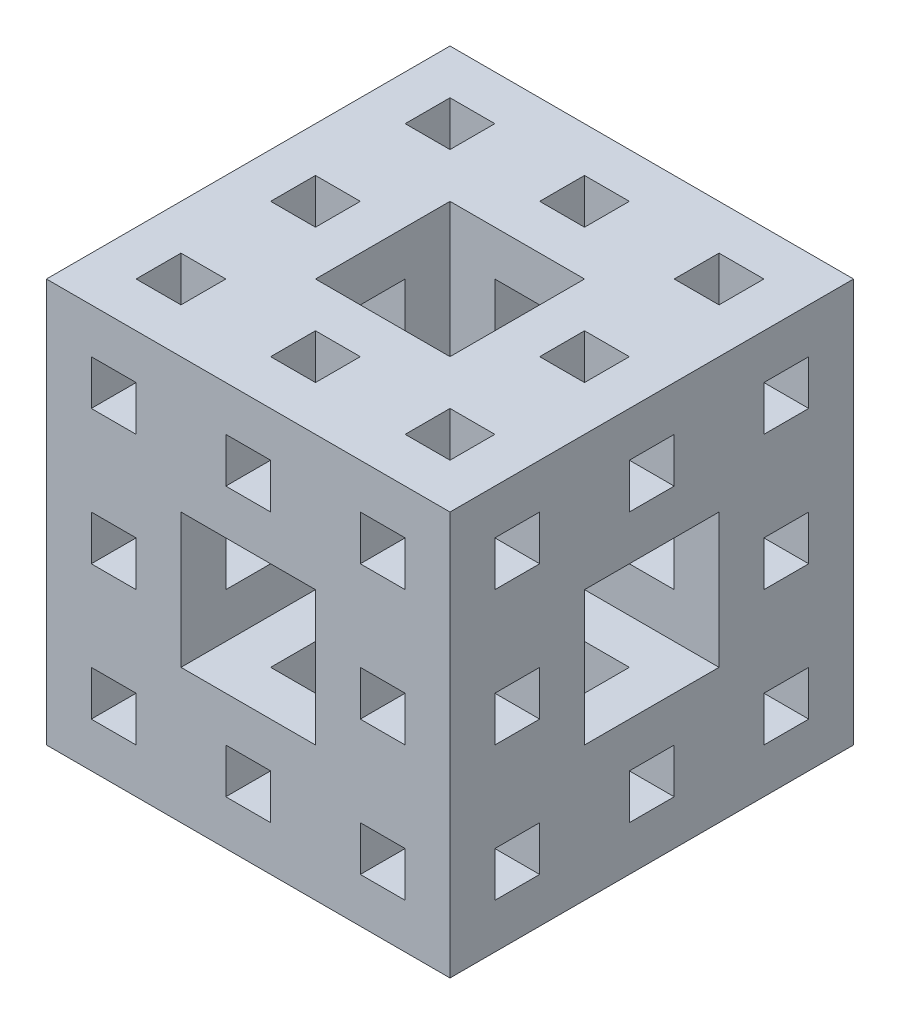
SolidWorks part; units mm, degrees
ref_plane "前视基准面" through (0, 0, 0) normal (0, 0, 1) x (1, 0, 0)
ref_plane "上视基准面" through (0, 0, 0) normal (0, 1, 0) x (1, 0, 0)
ref_plane "右视基准面" through (0, 0, 0) normal (1, 0, 0) x (0, 0, -1)
sketch "草图1" plane through (0, 0, 0) normal (0, 0, 1) x (1, 0, 0)
  line L0 (0, 0) -> (81, 0)
  line L1 (81, 0) -> (81, 81)
  line L2 (81, 81) -> (0, 81)
  line L3 (0, 81) -> (0, 0)
extrude "凸台-拉伸1" add sketch "草图1" along normal blind 81
sketch "草图2" plane through (0, 0, 0) normal (1, 0, 0) x (0, 0, -1)
  line L0 (-27, 27) -> (-54, 27)
  line L1 (-54, 27) -> (-54, 54)
  line L2 (-54, 54) -> (-27, 54)
  line L3 (-27, 54) -> (-27, 27)
extrude "切除-拉伸1" cut sketch "草图2" along normal through all
sketch "草图3" plane through (0, 0, 0) normal (0, 1, 0) x (1, 0, 0)
  line L0 (27, -27) -> (54, -27)
  line L1 (54, -27) -> (54, -54)
  line L2 (54, -54) -> (27, -54)
  line L3 (27, -54) -> (27, -27)
extrude "切除-拉伸2" cut sketch "草图3" along normal through all
sketch "草图4" plane through (0, 0, 0) normal (0, 0, 1) x (1, 0, 0)
  line L0 (27, 27) -> (54, 27)
  line L1 (54, 27) -> (54, 54)
  line L2 (54, 54) -> (27, 54)
  line L3 (27, 54) -> (27, 27)
extrude "切除-拉伸3" cut sketch "草图4" along normal through all
sketch "草图5" plane through (0, 0, 0) normal (1, 0, 0) x (0, 0, -1)
  line L0 (-9, 9) -> (-18, 9)
  line L1 (-18, 9) -> (-18, 18)
  line L2 (-18, 18) -> (-9, 18)
  line L3 (-9, 18) -> (-9, 9)
  line L4 (-36, 9) -> (-45, 9)
  line L5 (-45, 9) -> (-45, 18)
  line L6 (-45, 18) -> (-36, 18)
  line L7 (-36, 18) -> (-36, 9)
  line L8 (-63, 9) -> (-72, 9)
  line L9 (-72, 9) -> (-72, 18)
  line L10 (-72, 18) -> (-63, 18)
  line L11 (-63, 18) -> (-63, 9)
  line L12 (-9, 36) -> (-18, 36)
  line L13 (-18, 36) -> (-18, 45)
  line L14 (-18, 45) -> (-9, 45)
  line L15 (-9, 45) -> (-9, 36)
  line L16 (-63, 36) -> (-72, 36)
  line L17 (-72, 36) -> (-72, 45)
  line L18 (-72, 45) -> (-63, 45)
  line L19 (-63, 45) -> (-63, 36)
  line L20 (-9, 63) -> (-18, 63)
  line L21 (-18, 63) -> (-18, 72)
  line L22 (-18, 72) -> (-9, 72)
  line L23 (-9, 72) -> (-9, 63)
  line L24 (-36, 63) -> (-45, 63)
  line L25 (-45, 63) -> (-45, 72)
  line L26 (-45, 72) -> (-36, 72)
  line L27 (-36, 72) -> (-36, 63)
  line L28 (-63, 63) -> (-72, 63)
  line L29 (-72, 63) -> (-72, 72)
  line L30 (-72, 72) -> (-63, 72)
  line L31 (-63, 72) -> (-63, 63)
extrude "切除-拉伸4" cut sketch "草图5" along normal through all
sketch "草图6" plane through (0, 0, 0) normal (0, 1, 0) x (1, 0, 0)
  line L0 (9, -9) -> (18, -9)
  line L1 (18, -9) -> (18, -18)
  line L2 (18, -18) -> (9, -18)
  line L3 (9, -18) -> (9, -9)
  line L4 (36, -9) -> (45, -9)
  line L5 (45, -9) -> (45, -18)
  line L6 (45, -18) -> (36, -18)
  line L7 (36, -18) -> (36, -9)
  line L8 (63, -9) -> (72, -9)
  line L9 (72, -9) -> (72, -18)
  line L10 (72, -18) -> (63, -18)
  line L11 (63, -18) -> (63, -9)
  line L12 (9, -36) -> (18, -36)
  line L13 (18, -36) -> (18, -45)
  line L14 (18, -45) -> (9, -45)
  line L15 (9, -45) -> (9, -36)
  line L16 (63, -36) -> (72, -36)
  line L17 (72, -36) -> (72, -45)
  line L18 (72, -45) -> (63, -45)
  line L19 (63, -45) -> (63, -36)
  line L20 (9, -63) -> (18, -63)
  line L21 (18, -63) -> (18, -72)
  line L22 (18, -72) -> (9, -72)
  line L23 (9, -72) -> (9, -63)
  line L24 (36, -63) -> (45, -63)
  line L25 (45, -63) -> (45, -72)
  line L26 (45, -72) -> (36, -72)
  line L27 (36, -72) -> (36, -63)
  line L28 (63, -63) -> (72, -63)
  line L29 (72, -63) -> (72, -72)
  line L30 (72, -72) -> (63, -72)
  line L31 (63, -72) -> (63, -63)
extrude "切除-拉伸5" cut sketch "草图6" along normal through all
sketch "草图7" plane through (0, 0, 0) normal (0, 0, 1) x (1, 0, 0)
  line L0 (9, 9) -> (18, 9)
  line L1 (18, 9) -> (18, 18)
  line L2 (18, 18) -> (9, 18)
  line L3 (9, 18) -> (9, 9)
  line L4 (36, 9) -> (45, 9)
  line L5 (45, 9) -> (45, 18)
  line L6 (45, 18) -> (36, 18)
  line L7 (36, 18) -> (36, 9)
  line L8 (63, 9) -> (72, 9)
  line L9 (72, 9) -> (72, 18)
  line L10 (72, 18) -> (63, 18)
  line L11 (63, 18) -> (63, 9)
  line L12 (9, 36) -> (18, 36)
  line L13 (18, 36) -> (18, 45)
  line L14 (18, 45) -> (9, 45)
  line L15 (9, 45) -> (9, 36)
  line L16 (63, 36) -> (72, 36)
  line L17 (72, 36) -> (72, 45)
  line L18 (72, 45) -> (63, 45)
  line L19 (63, 45) -> (63, 36)
  line L20 (9, 63) -> (18, 63)
  line L21 (18, 63) -> (18, 72)
  line L22 (18, 72) -> (9, 72)
  line L23 (9, 72) -> (9, 63)
  line L24 (36, 63) -> (45, 63)
  line L25 (45, 63) -> (45, 72)
  line L26 (45, 72) -> (36, 72)
  line L27 (36, 72) -> (36, 63)
  line L28 (63, 63) -> (72, 63)
  line L29 (72, 63) -> (72, 72)
  line L30 (72, 72) -> (63, 72)
  line L31 (63, 72) -> (63, 63)
extrude "切除-拉伸6" cut sketch "草图7" along normal through all
